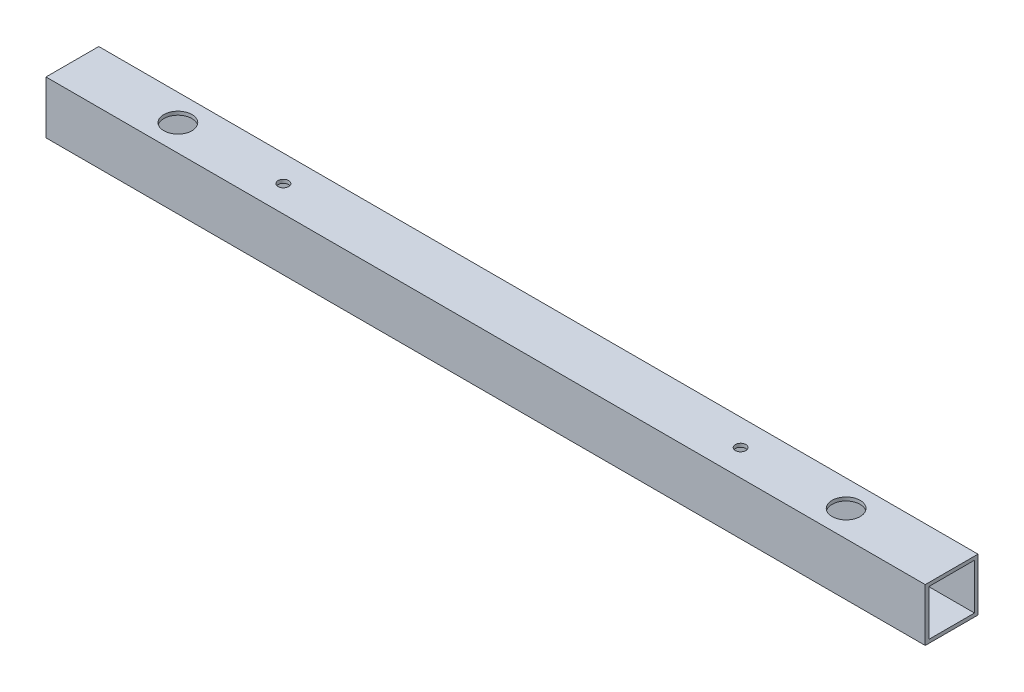
SolidWorks part; units mm, degrees
ref_plane "前视基准面" through (0, 0, 0) normal (0, 0, 1) x (1, 0, 0)
ref_plane "上视基准面" through (0, 0, 0) normal (0, 1, 0) x (1, 0, 0)
ref_plane "右视基准面" through (0, 0, 0) normal (1, 0, 0) x (0, 0, -1)
sketch "草图1" plane through (0, 0, 0) normal (1, 0, 0) x (0, 0, -1)
  line L0 (-6.5, 6.5) -> (6.5, 6.5)
  line L1 (-7.5, -7.5) -> (7.5, -7.5)
  line L2 (-7.5, -7.5) -> (-7.5, 7.5)
  line L3 (-7.5, 7.5) -> (7.5, 7.5)
  line L4 (7.5, -7.5) -> (7.5, 7.5)
  line L5 (-7.5, -7.5) -> (7.5, 7.5) construction
  line L6 (-7.5, 7.5) -> (7.5, -7.5) construction
  line L7 (6.5, -6.5) -> (6.5, 6.5)
  line L8 (-6.5, -6.5) -> (6.5, -6.5)
  line L9 (-6.5, -6.5) -> (-6.5, 6.5)
  point P0 (0, 0)
  dimension "D1" = 15
  dimension "D2" = 15
  dimension "D3" = 1
extrude "凸台-拉伸1" add sketch "草图1" along normal blind 250
sketch "草图2" plane through (0, 7.5, 0) normal (0, 1, 0) x (1, 0, 0)
  line L0 (0, 7.5) -> (0, -7.5) construction
  line L1 (125, 19.5188) -> (125, -36.4378) construction
  circle A0 centre (30, 0) radius 1.5
  circle A1 centre (60, 0) radius 1.5
  circle A2 centre (190, 0) radius 1.5
  circle A3 centre (220, 0) radius 1.5
  dimension "D1" = 60
  dimension "D2" = 30
extrude "切除-拉伸1" cut sketch "草图2" against normal blind 250
sketch "草图3" plane through (0, 7.5, 0) normal (0, 1, 0) x (1, 0, 0)
  circle A0 centre (30, 0) radius 4
  circle A1 centre (220, 0) radius 4
extrude "切除-拉伸2" cut sketch "草图3" against normal blind 10
sketch "草图4" plane through (0, -7.5, 0) normal (0, -1, 0) x (1, 0, 0)
  circle A0 centre (60, 0) radius 4
  circle A1 centre (190, 0) radius 4
extrude "切除-拉伸3" cut sketch "草图4" against normal blind 10
